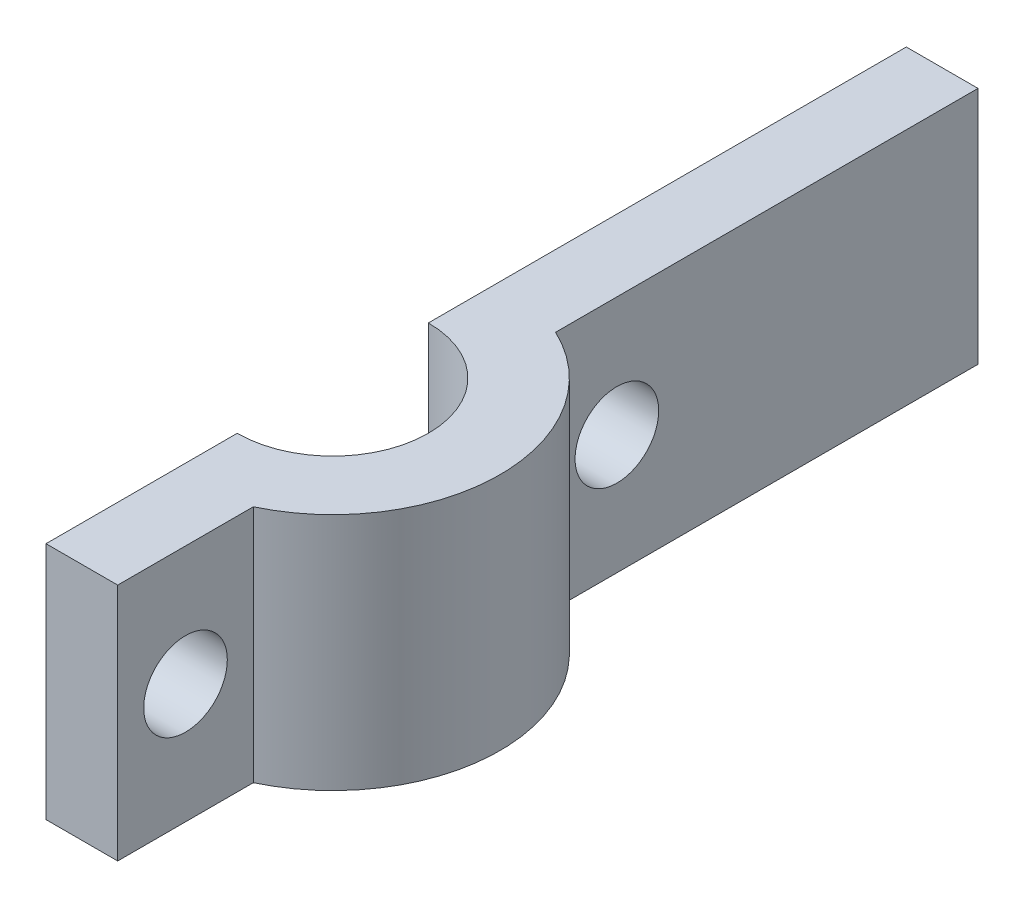
SolidWorks part; units mm, degrees
ref_plane "前视基准面" through (0, 0, 0) normal (0, 0, 1) x (1, 0, 0)
ref_plane "上视基准面" through (0, 0, 0) normal (0, 1, 0) x (1, 0, 0)
ref_plane "右视基准面" through (0, 0, 0) normal (1, 0, 0) x (0, 0, -1)
sketch "草图1" plane through (0, 0, 0) normal (0, 1, 0) x (1, 0, 0)
  line L0 (0, 24) -> (0, 4)
  line L1 (0, -4) -> (0, -12)
  line L2 (3, 24) -> (3, 6.3246)
  line L3 (3, -6.3246) -> (3, -12)
  line L4 (0, -12) -> (3, -12)
  line L5 (3, 24) -> (0, 24)
  arc A0 (0, -4) -> (0, 4) centre (0, 0) ccw
  arc A1 (3, -6.3246) -> (3, 6.3246) centre (0, 0) ccw
  dimension "D1" = 8
  dimension "D2" = 8
  dimension "D3" = 20
  dimension "D4" = 3
extrude "凸台-拉伸1" add sketch "草图1" along normal blind 10
sketch "草图2" plane through (3, 0, 0) normal (1, 0, 0) x (0, 0, -1)
  line L0 (-12, 5) -> (24, 5) construction
  line L1 (-12, 10) -> (-12, 0) construction
  line L2 (24, 10) -> (24, 0) construction
  circle A0 centre (-9.1623, 5) radius 1.75
  circle A1 centre (8.889, 5) radius 1.75
  dimension "D1" = 3.5
  dimension "D2" = 3.5
extrude "切除-拉伸1" cut sketch "草图2" against normal through all
